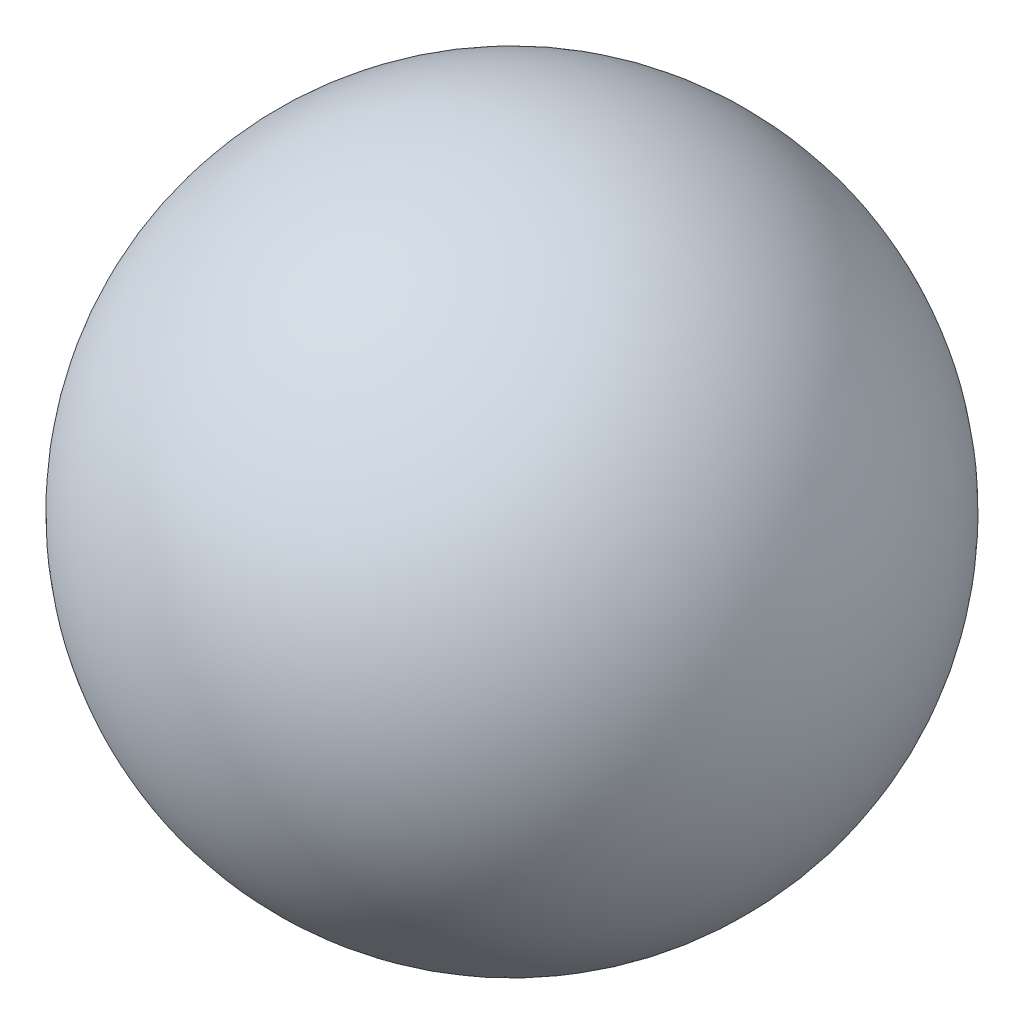
SolidWorks part; units mm, degrees
ref_plane "前视基准面" through (0, 0, 0) normal (0, 0, 1) x (1, 0, 0)
ref_plane "上视基准面" through (0, 0, 0) normal (0, 1, 0) x (1, 0, 0)
ref_plane "右视基准面" through (0, 0, 0) normal (1, 0, 0) x (0, 0, -1)
other "Configuration Table"
sketch "草图1" plane through (0, 0, 0) normal (0, 1, 0) x (1, 0, 0)
  line L0 (0, 7.3) -> (0, -7.3)
  arc A0 (0, -7.3) -> (0, 7.3) centre (0, 0) ccw
revolve "旋转1" add sketch "草图1" angle 360 about L0
